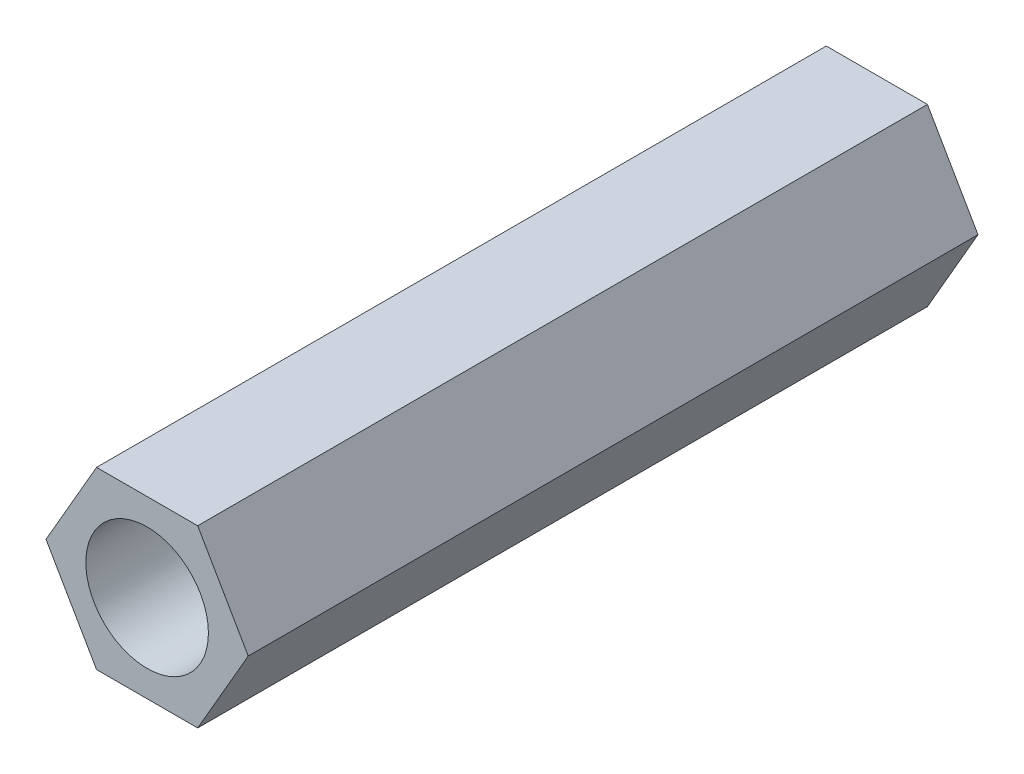
SolidWorks part; units mm, degrees
ref_plane "前视基准面" through (0, 0, 0) normal (0, 0, 1) x (1, 0, 0)
ref_plane "上视基准面" through (0, 0, 0) normal (0, 1, 0) x (1, 0, 0)
ref_plane "右视基准面" through (0, 0, 0) normal (1, 0, 0) x (0, 0, -1)
sketch "草图1" plane through (0, 0, 0) normal (0, 0, 1) x (1, 0, 0)
  line L1 (1.7321, 3) -> (-1.7321, 3)
  line L2 (-1.7321, 3) -> (-3.4641, 0)
  line L3 (-3.4641, 0) -> (-1.7321, -3)
  line L4 (-1.7321, -3) -> (1.7321, -3)
  line L5 (1.7321, -3) -> (3.4641, 0)
  line L6 (3.4641, 0) -> (1.7321, 3)
  circle A0 centre (0, 0) radius 2.1
  circle A1 centre (0, 0) radius 3 construction
  dimension "D2" = 4.2
  dimension "D1" = 6
extrude "凸台-拉伸1" add sketch "草图1" along normal blind 25
